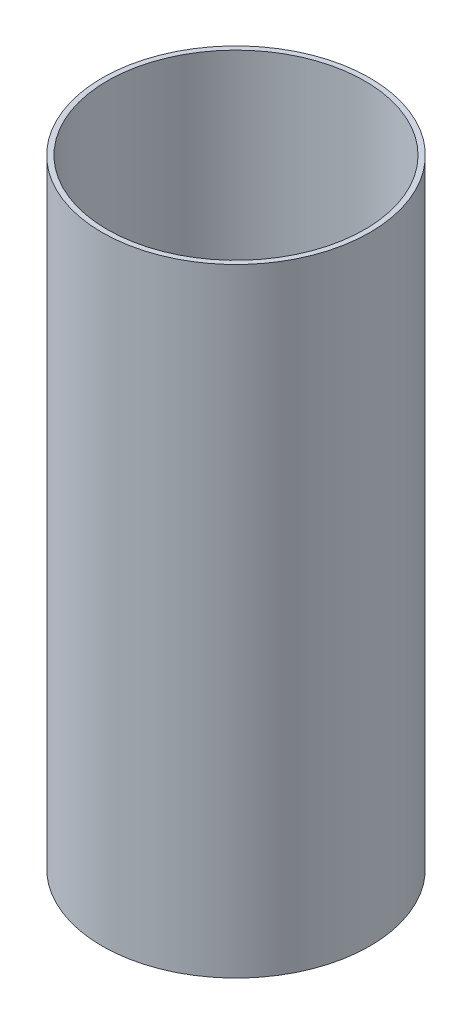
SolidWorks part; units mm, degrees
material "Plástico personalizado"
ref_plane "Plano frontal" through (0, 0, 0) normal (0, 0, 1) x (1, 0, 0)
ref_plane "Plano superior" through (0, 0, 0) normal (0, 1, 0) x (1, 0, 0)
ref_plane "Plano direito" through (0, 0, 0) normal (1, 0, 0) x (0, 0, -1)
sketch "Esboço1" plane through (0, 0, 0) normal (0, 1, 0) x (1, 0, 0)
  circle A0 centre (0, 0) radius 26
  circle A1 centre (0, 0) radius 25
extrude "Ressalto-extrusão1" add sketch "Esboço1" along normal blind 120
